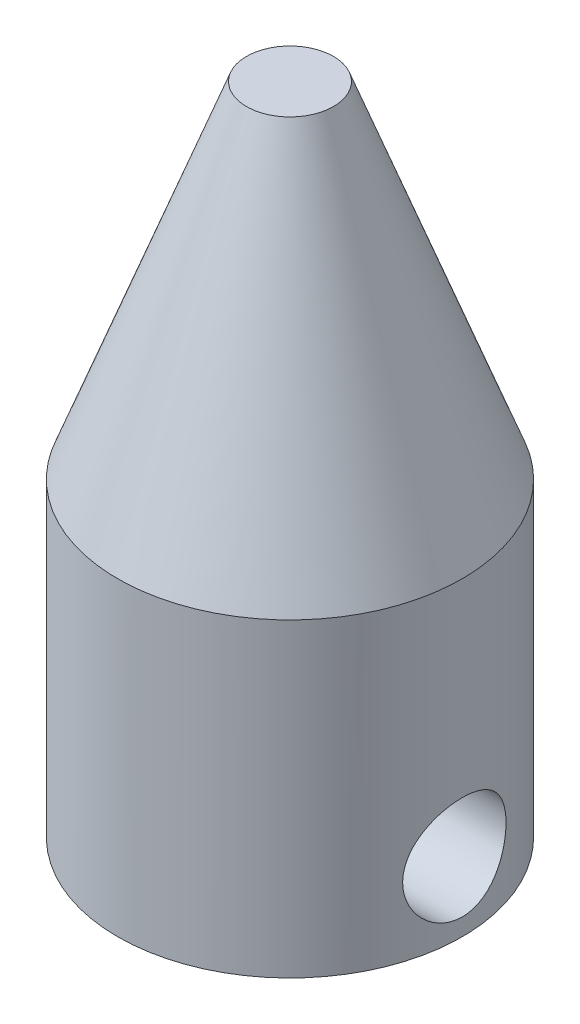
SolidWorks part; units mm, degrees
ref_plane "Front Plane" through (0, 0, 0) normal (0, 0, 1) x (1, 0, 0)
ref_plane "Top Plane" through (0, 0, 0) normal (0, 1, 0) x (1, 0, 0)
ref_plane "Right Plane" through (0, 0, 0) normal (1, 0, 0) x (0, 0, -1)
sketch "Sketch1" plane through (0, 0, 0) normal (0, 1, 0) x (1, 0, 0)
  circle A0 centre (0, 0) radius 5
  dimension "D1" = 10
extrude "body" add sketch "Sketch1" along normal blind 9
sketch "Sketch2" plane through (0, 0, 0) normal (1, 0, 0) x (0, 0, -1)
  circle A0 centre (0, 2) radius 1.5
  dimension "D1" = 2
  dimension "D2" = 3
extrude "pin insert" cut sketch "Sketch2" against normal through all and the other way through all
ref_plane "contact plane" through (0, 19, 0) normal (0, 1, 0) x (1, 0, 0)
sketch "head SA" plane through (0, 19, 0) normal (0, 1, 0) x (1, 0, 0)
  circle A0 centre (0, 0) radius 1.262
  dimension "D1" = 2.524
loft "cone" add profiles "head SA" section "head SA" section face at (0, 9, 5)
